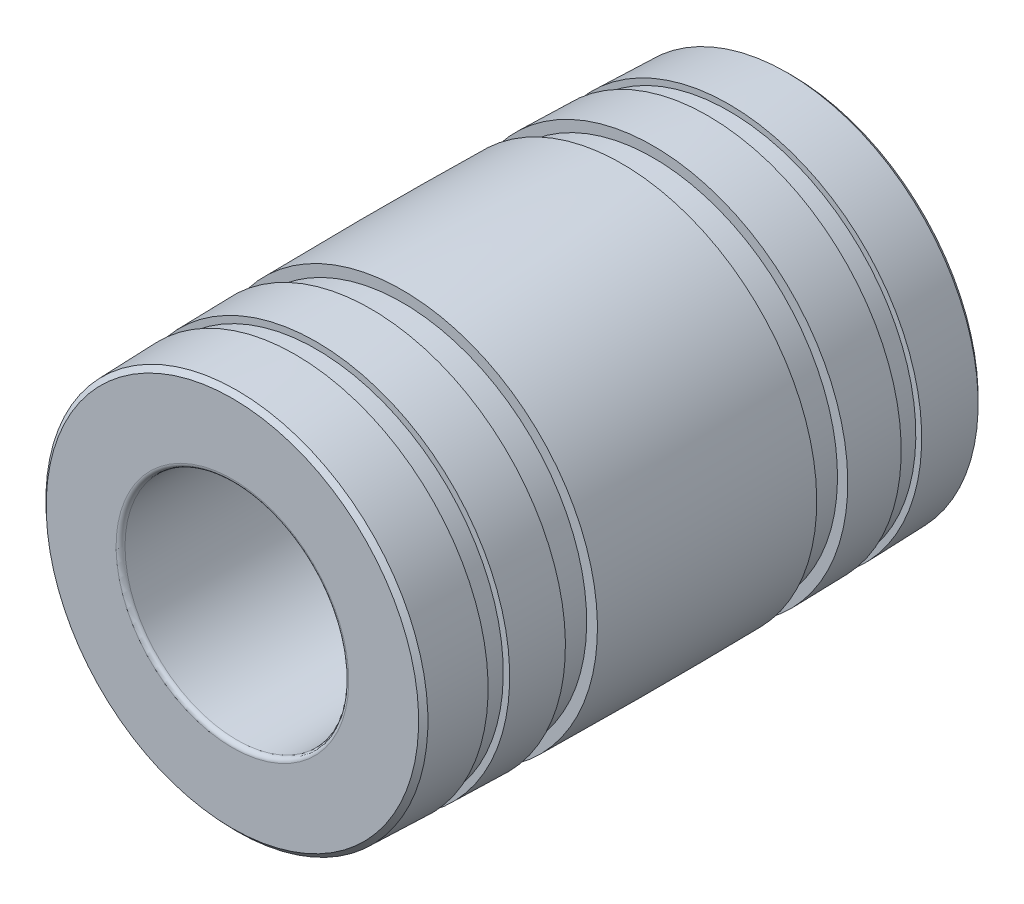
SolidWorks part; units mm, degrees
ref_plane "Front" through (0, 0, 0) normal (0, 0, 1) x (1, 0, 0)
ref_plane "Top" through (0, 0, 0) normal (0, 1, 0) x (1, 0, 0)
ref_plane "Right" through (0, 0, 0) normal (1, 0, 0) x (0, 0, -1)
sketch "Sketch1" plane through (0, 0, 0) normal (1, 0, 0) x (0, 0, -1)
  line L0 (-15.875, 0) -> (15.875, 0)
  line L1 (-15.875, 0) -> (-15.875, -10.8347)
  line L2 (0, 0) -> (0, -11.1125) construction
  line L3 (-15.875, -10.8347) -> (-15.875, 10.8347) construction
  line L4 (-12.3063, -10.9456) -> (-12.3063, -10.6122)
  line L5 (-12.3063, -10.6122) -> (-11.1125, -10.6122)
  line L6 (-11.1125, -10.6122) -> (-11.1125, -10.9764)
  line L7 (-15.875, -11.1125) -> (-15.875, 11.1125) construction
  line L8 (12.3063, -10.6122) -> (15.875, -10.6122) construction
  line L9 (15.875, -10.6122) -> (15.875, 10.6122) construction
  line L10 (15.875, 0) -> (15.875, -10.8347)
  line L11 (-11.1125, -11.1125) -> (11.1125, -11.1125) construction
  line L12 (-8.0137, -11.0417) -> (-8.0137, -10.4583)
  line L13 (-8.0137, -10.4583) -> (-6.223, -10.4583)
  line L14 (-6.223, -10.4583) -> (-6.223, -11.0698)
  line L15 (-6.223, -10.4583) -> (0, -10.4583) construction
  line L16 (11.1125, -10.6122) -> (11.1125, -10.9764)
  line L17 (12.3063, -10.6122) -> (11.1125, -10.6122)
  line L18 (12.3063, -10.9456) -> (12.3063, -10.6122)
  line L19 (0, -10.4583) -> (6.223, -10.4583) construction
  line L20 (-11.1125, -10.6122) -> (-8.0137, -10.6122) construction
  line L21 (11.1125, -10.6122) -> (8.0137, -10.6122) construction
  line L22 (6.223, -11.0698) -> (6.223, -10.4583)
  line L23 (6.223, -10.4583) -> (8.0137, -10.4583)
  line L24 (8.0137, -10.4583) -> (8.0137, -11.0417)
  line L25 (-12.3063, -10.9456) -> (12.3063, -10.9456) construction
  arc A0 (0, -11.1125) -> (-6.223, -11.0698) centre (0, 442.5978) cw
  arc A1 (0, -11.1125) -> (6.223, -11.0698) centre (0, 442.5978) ccw
  arc A2 (-8.0137, -11.0417) -> (-11.1125, -10.9764) centre (0, 442.5978) cw
  arc A3 (-12.3063, -10.9456) -> (-15.875, -10.8347) centre (0, 442.5978) cw
  arc A4 (8.0137, -11.0417) -> (11.1125, -10.9764) centre (0, 442.5978) ccw
  arc A5 (12.3063, -10.9456) -> (15.875, -10.8347) centre (0, 442.5978) ccw
  point P13 (15.875, 11.1125)
  dimension "D1" = 1.7907
  dimension "Overall Lg B" = 31.75
  dimension "D2" = 0.3334
  dimension "D3" = 0.5834
  dimension "D4" = 21.6694
  dimension "D5" = 1.1938
  dimension "Lg C" = 24.6126
  dimension "OD A" = 22.225
  dimension "Supplier D Between Retaining Rings" = 22.225
  dimension "Supplier E Between O-Rings" = 12.446
revolve "Bearing" add sketch "Sketch1" angle 360 mid plane about L0
sketch "Sketch2" plane through (0, 0, 0) normal (0, 0, 1) x (1, 0, 0)
  circle A0 centre (0, 0) radius 6.35
  circle A1 centre (0, 0) radius 11.1125 construction
  dimension "For Shaft Dia" = 12.7
extrude "Bore" cut sketch "Sketch2" against normal through all and the other way through all
chamfer "OD Chamfer" distance 0.254 angle 45 2 edges at (0, -10.8347, -15.875) (0, -10.8347, 15.875)
fillet "ID Fillet" radius 0.254 2 edges at (6.35, 0, -15.875) (6.35, 0, 15.875)
sketch "Retaining Hole" [suppressed] plane through (0, 0, 0) normal (1, 0, 0) x (0, 0, -1)
  line L0 (-15.875, -10.8347) -> (-15.875, 10.8347) construction
  line L1 (-15.875, 0) -> (15.875, 0) construction
  circle A0 centre (0, 0) radius 1.6891
  dimension "Supplier H Hole Dia" = 3.3782
  dimension "Supplier I Hole Locate" = 15.875
extrude "Retaining Hole " [suppressed] cut sketch "Retaining Hole" along normal through all
sketch "Slot Opening" [suppressed] plane through (0, 0, 0) normal (0, 0, 1) x (1, 0, 0)
  line L0 (0, -38.1) -> (0, -3.2029) construction
  line L1 (-12.7, -21.997) -> (12.7, -21.997)
  line L2 (-12.7, -21.997) -> (-21.997, -38.1)
  line L3 (-21.997, -38.1) -> (21.997, -38.1)
  line L4 (21.997, -38.1) -> (12.7, -21.997)
  circle A2 centre (0, 0) radius 25.4 construction
  dimension "D1" = 60
  dimension "Wd E" = 3.175
extrude "Slot Opening " [suppressed] cut sketch "Slot Opening" against normal through all and the other way through all
other "Move Face1" [suppressed] parameters "D1"=3.175
other "Move Face2" [suppressed] parameters "D1"=15
sketch "Ref" [suppressed] plane through (0, 0, 0) normal (0, 0, 1) x (1, 0, 0)
  line L0 (13.0254, 5.2388) -> (7.0543, 3.6389) construction
  line L1 (13.2667, 5.3035) -> (7.0543, 3.6389) construction
  line L2 (7.9286, 0.3758) -> (13.8998, 1.9757) construction
  line L3 (7.9286, 0.3758) -> (14.1411, 2.0404) construction
  line L4 (7.667, 2.0544) -> (13.8007, 3.6979) construction
  line L5 (0, 0) -> (14.2875, 0) construction
  circle A0 centre (0, 0) radius 14.2875 construction
  arc A1 (14.1411, 2.0404) -> (13.2667, 5.3035) centre (0, 0) ccw construction
  circle A2 centre (0, 0) radius 7.9375 construction
  arc A3 (7.9286, 0.3758) -> (7.0543, 3.6389) centre (0, 0) ccw construction
equation "\"D1@Sketch1\" = \"D5@Sketch1\" * 1.5"
equation "\"D4@Sketch1\" = \"OD A@Sketch1\" * .975"
equation "\"D2@Sketch1\" = \"OD A@Sketch1\" * .015"
equation "\"D3@Sketch1\" = \"D2@Sketch1\" * 1.75"
